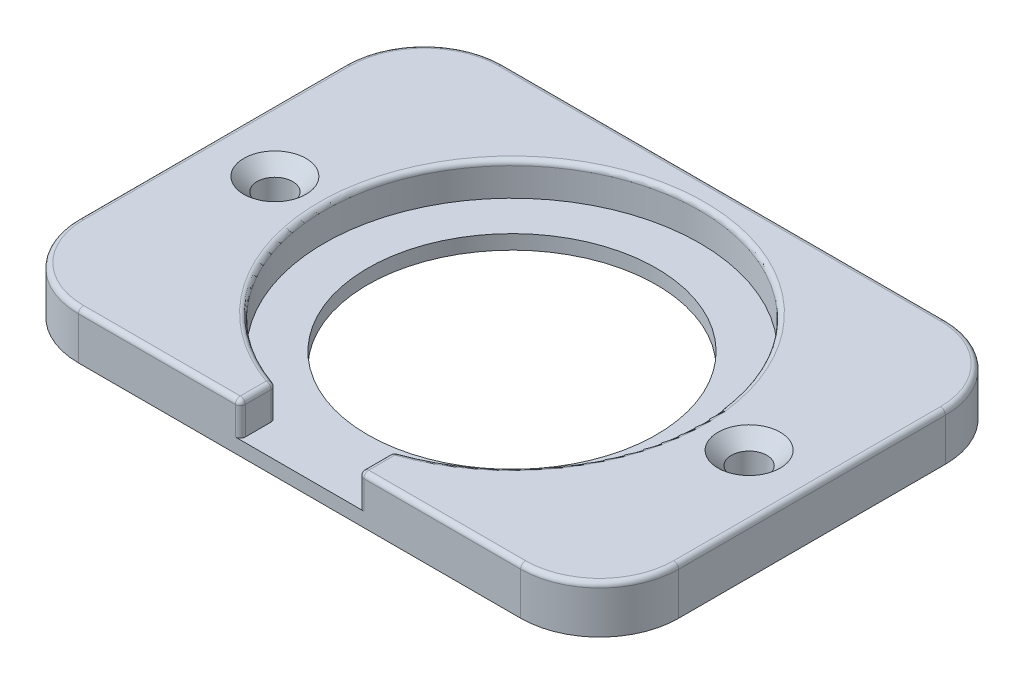
SolidWorks part; units mm, degrees
material "ABS"
ref_plane "Front" through (0, 0, 0) normal (0, 0, 1) x (1, 0, 0)
ref_plane "Top" through (0, 0, 0) normal (0, 1, 0) x (1, 0, 0)
ref_plane "Side" through (0, 0, 0) normal (1, 0, 0) x (0, 0, -1)
sketch "Sketch1" plane through (0, 0, 0) normal (0, 1, 0) x (1, 0, 0)
  line L1 (-30.375, -21.5) -> (30.375, -21.5)
  line L2 (-30.375, -21.5) -> (-30.375, 21.5)
  line L3 (-30.375, 21.5) -> (30.375, 21.5)
  line L4 (30.375, -21.5) -> (30.375, 21.5)
  line L5 (-30.375, -21.5) -> (30.375, 21.5) construction
  line L6 (-30.375, 21.5) -> (30.375, -21.5) construction
  point P0 (0, 0)
  dimension "D1" = 60.75
  dimension "D2" = 43
extrude "Boss-Extrude1" add sketch "Sketch1" along normal blind 4.8
fillet "Fillet1" radius 8 4 edges at (-30.375, 2.4, -21.5) (30.375, 2.4, -21.5) (30.375, 2.4, 21.5) (-30.375, 2.4, 21.5)
sketch "Sketch2" plane through (0, 4.8, 0) normal (0, 1, 0) x (1, 0, 0)
  circle A0 centre (0, 0) radius 19
  dimension "D1" = 38
extrude "Cut-Extrude1" cut sketch "Sketch2" against normal blind 3.35
sketch "Sketch3" plane through (0, 1.45, 0) normal (0, 1, 0) x (1, 0, 0)
  circle A0 centre (0, 0) radius 14.61
  dimension "D1" = 29.22
extrude "Cut-Extrude2" cut sketch "Sketch3" against normal through all
sketch "Sketch4" plane through (0, 4.8, 0) normal (0, 1, 0) x (1, 0, 0)
  line L1 (-6, -24.5145) -> (6, -24.5145)
  line L2 (-6, -24.5145) -> (-6, -13.4855)
  line L3 (-6, -13.4855) -> (6, -13.4855)
  line L4 (6, -24.5145) -> (6, -13.4855)
  line L5 (-6, -24.5145) -> (6, -13.4855) construction
  line L6 (-6, -13.4855) -> (6, -24.5145) construction
  circle A0 centre (0, 0) radius 19 construction
  point P0 (0, -19)
  dimension "D1" = 12
extrude "Cut-Extrude3" cut sketch "Sketch4" against normal up to surface (3.35 mm away) up to face at (0, 1.45, 14.61)
hole_wizard "CSK for M3 Flat Head Machine Screw1" positions "Sketch5" profile "Sketch6" countersink size "M3" standard "ANSI Metric" end condition through all
sketch "Sketch5" plane through (0, 4.8, 0) normal (0, 1, 0) x (1, 0, 0)
  point P0 (-24, 0)
  point P3 (0, 0)
  dimension "D1" = 24
sketch "Sketch6" plane through (-24, 4.8, 0) normal (1, 0, 0) x (0, 0, 1)
  line L0 (0, 0) -> (0, 4.8)
  line L1 (0, 4.8) -> (1.8, 4.8)
  line L2 (1.8, 4.8) -> (1.8, 1.35)
  line L3 (1.8, 1.35) -> (3.15, 0)
  line L5 (3.15, 0) -> (0, 0)
  line L6 (-1.8, 1.35) -> (-3.15, 0) construction
  line L11 (0, -6.35) -> (0, 107.95) construction
  dimension "Thru Hole Dia." = 3.6
  dimension "Thru Hole Depth" = 4.8
  dimension "Near C'Sink Dia." = 6.3
  dimension "Near C'Sink Angle" = 90
mirror "Mirror1" about plane through (0, 0, 0) normal (1, 0, 0) of "CSK for M3 Flat Head Machine Screw1"
fillet "Fillet2" radius 0.5 16 edges at (14.1875, 4.8, 21.5) (28.0319, 4.8, 19.1569) (30.375, 4.8, 0) (28.0319, 4.8, -19.1569) (0, 4.8, -21.5) (-28.0319, 4.8, -19.1569) (-14.1875, 4.8, 21.5) (-28.0319, 4.8, 19.1569) (6, 3.125, 21.5) (6, 3.125, 18.0278) (-6, 3.125, 18.0278) (-6, 3.125, 21.5) (6, 4.8, 19.7639) (-6, 4.8, 19.7639) (0, 4.8, -19) (-30.375, 4.8, 0)
